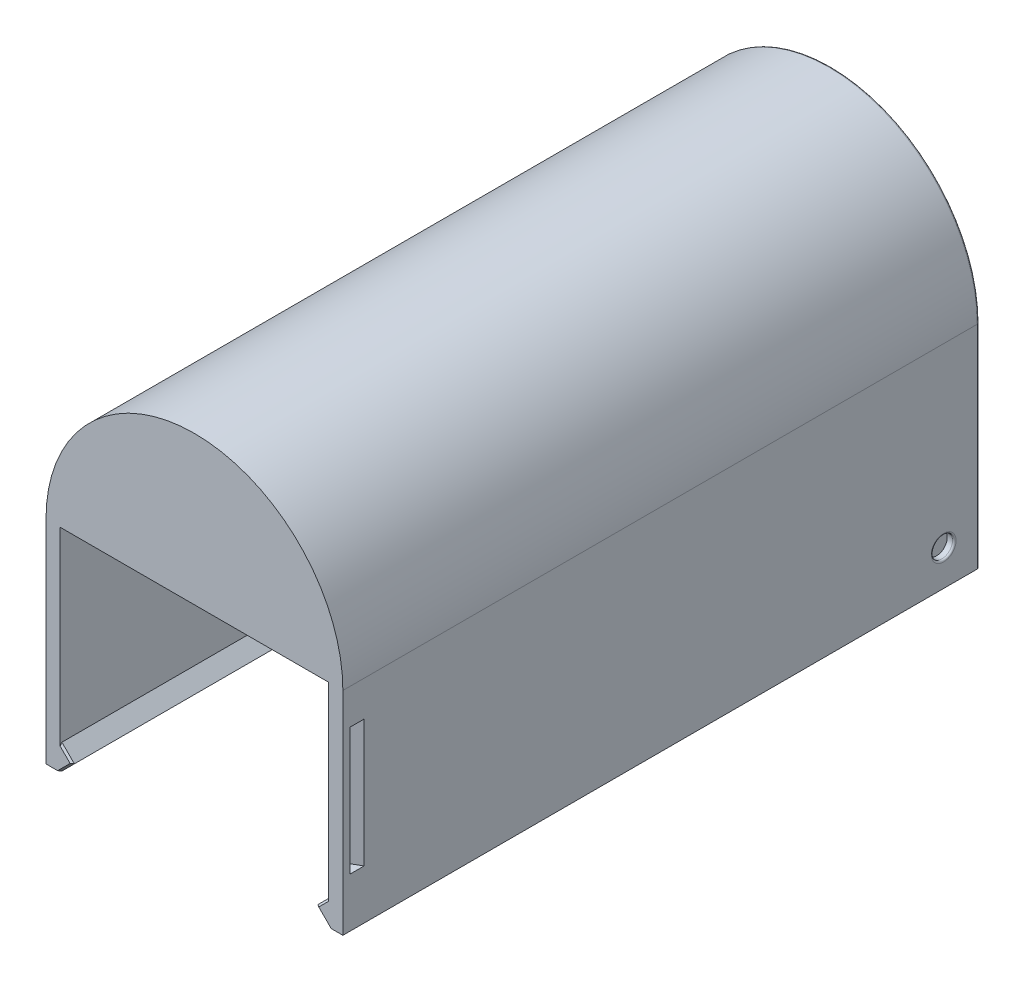
SolidWorks part; units mm, degrees
ref_plane "Front Plane" through (0, 0, 0) normal (0, 0, 1) x (1, 0, 0)
ref_plane "Top Plane" through (0, 0, 0) normal (0, 1, 0) x (1, 0, 0)
ref_plane "Right Plane" through (0, 0, 0) normal (1, 0, 0) x (0, 0, -1)
sketch "Sketch2" plane through (0, 0, 0) normal (0, 0, 1) x (1, 0, 0)
  line L0 (0, 0) -> (0, 30)
  line L1 (42, 0) -> (42, 30)
  line L2 (2, 0) -> (2, 30)
  line L3 (40, 0) -> (40, 30)
  line L4 (0, 0) -> (2, 0)
  line L5 (42, 0) -> (40, 0)
  line L6 (0, 0) -> (42, 0) construction
  line L7 (21, 0) -> (21, 51) construction
  arc A0 (42, 30) -> (0, 30) centre (21, 30) ccw
  arc A1 (40, 30) -> (2, 30) centre (21, 30) ccw
  dimension "D1" = 30
  dimension "D2" = 42
  dimension "D4" = 51
  dimension "D3" = 2
extrude "Boss-Extrude1" add sketch "Sketch2" along normal blind 90
sketch "Sketch3" plane through (0, 0, 90) normal (0, 0, 1) x (1, 0, 0)
  line L0 (2, 30) -> (40, 30)
  arc A0 (40, 30) -> (2, 30) centre (21, 30) ccw
extrude "Boss-Extrude2" add sketch "Sketch3" against normal blind 1
sketch "Sketch5" plane through (0, 0, 0) normal (-1, 0, 0) x (0, 0, 1)
  line L0 (20.5, 17.5) -> (24.5, 17.5) construction
  line L1 (20.5, 23) -> (24.5, 23)
  line L2 (20.5, 12) -> (24.5, 12)
  line L3 (0, 30) -> (0, 0) construction
  line L4 (90, 0) -> (0, 0) construction
  arc A0 (20.5, 23) -> (20.5, 12) centre (20.5, 17.5) ccw
  arc A1 (24.5, 12) -> (24.5, 23) centre (24.5, 17.5) ccw
  point P2 (22.5, 17.5)
  point P7 (30, 17.5)
  point P8 (15, 17.5)
  dimension "D1" = 15
  dimension "D2" = 12
  dimension "D3" = 11
  dimension "D4" = 15
extrude "Cut-Extrude2" cut sketch "Sketch5" against normal up to surface (2 mm away) up to face at (2, 18, 53.8)
sketch "Sketch6" plane through (0, 0, 0) normal (-1, 0, 0) x (0, 0, 1)
  line L0 (90, 0) -> (0, 0) construction
  line L1 (0, 30) -> (0, 0) construction
  circle A0 centre (5, 5) radius 1.5
  dimension "D2" = 3
  dimension "D1" = 5
  dimension "D3" = 5
extrude "Cut-Extrude3" cut sketch "Sketch6" against normal blind 1
ref_plane "Plane1" through (21, 0, 0) normal (1, 0, 0) x (0, 0, -1)
mirror "Mirror1" about plane through (21, 0, 0) normal (1, 0, 0) of "Cut-Extrude3"
ref_plane "Plane2" through (0, 7, 0) normal (0, -1, 0) x (-1, 0, 0)
sketch "Sketch7" plane through (0, 7, 0) normal (0, -1, 0) x (-1, 0, 0)
  line L0 (0, -90) -> (0, -89) construction
  line L1 (0, -89) -> (0, -87)
  line L2 (0, -87) -> (-1.7321, -88)
  line L3 (-1.7321, -88) -> (0, -89)
  line L4 (0, -90) -> (0, 0) construction
  point P6 (0, 0)
  point P7 (0, -90)
  dimension "D1" = 1
  dimension "D2" = 2
  dimension "D3" = 0
  dimension "D4" = 60
  dimension "D5" = 60
extrude "Cut-Extrude4" cut sketch "Sketch7" against normal blind 18
mirror "Mirror2" about plane through (21, 0, 0) normal (1, 0, 0) of "Cut-Extrude4"
sketch "Sketch8" plane through (0, 0, 90) normal (0, 0, 1) x (1, 0, 0)
  line L0 (2, 0) -> (3.7678, 1.7678)
  line L2 (3.7678, 1.7678) -> (2, 3.5355)
  line L3 (2, 0) -> (2, 30) construction
  line L5 (2, 3.5355) -> (2, 0)
  dimension "D1" = 90
  dimension "D2" = 2.5
  dimension "D3" = 2.5
extrude "Boss-Extrude3" add sketch "Sketch8" against normal blind 78 contours L5 L0 L2
mirror "Mirror3" about plane through (21, 0, 0) normal (1, 0, 0) of "Boss-Extrude3"
sketch "Sketch9" plane through (0, 7, 0) normal (0, -1, 0) x (-1, 0, 0)
  line L0 (-2, -8) -> (-2, -14)
  line L1 (-2, -12) -> (-2, 0) construction
  line L2 (-2, -14) -> (-4.6458, -11)
  line L3 (-4.6458, -11) -> (-2, -8)
  line L4 (-2, -39) -> (-2, -45)
  line L5 (-2, -90) -> (-2, -12) construction
  line L6 (-2, -45) -> (-4.6458, -42)
  line L7 (-4.6458, -42) -> (-2, -39)
  line L8 (0, -15) -> (-2, -15) construction
  dimension "D1" = 6
  dimension "D2" = 6
  dimension "D3" = 4
  dimension "D4" = 4
  dimension "D5" = 4
  dimension "D6" = 4
  dimension "D7" = 25
  dimension "D8" = 1
extrude "Boss-Extrude4" add sketch "Sketch9" against normal blind 6 from offset 8 offset against normal yes
fillet "Fillet2" radius 0.25 2 edges at (42, 5, 6.5) (0, 5, 6.5)
chamfer "Chamfer1" distance 0.25 angle 45 6 edges at (39.1161, 0.8839, 90) (39.1161, 2.6517, 90) (2.8839, 0.8839, 90) (2.8839, 2.6517, 90) (2.8839, 2.6517, 12) (39.1161, 2.6517, 12)
fillet "Fillet3" radius 0.25 3 edges at (42, 15, 0) (0, 15, 0) (21, 51, 0)
chamfer "Chamfer2" distance 0.25 angle 45 2 edges at (2.7955, 0.7955, 12) (39.2045, 0.7955, 12)
